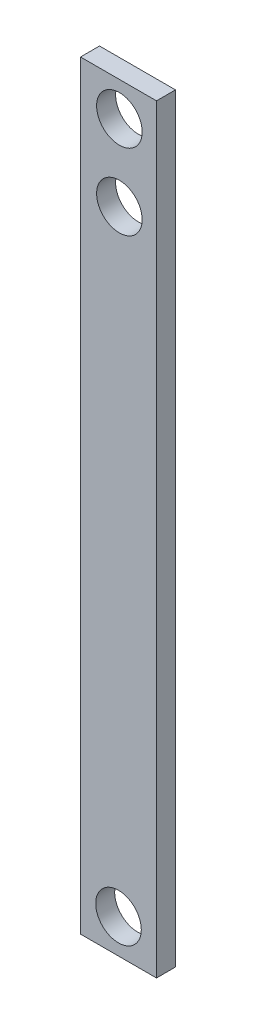
SolidWorks part; units mm, degrees
ref_plane "Front Plane" through (0, 0, 0) normal (0, 0, 1) x (1, 0, 0)
ref_plane "Top Plane" through (0, 0, 0) normal (0, 1, 0) x (1, 0, 0)
ref_plane "Right Plane" through (0, 0, 0) normal (1, 0, 0) x (0, 0, -1)
sketch "Sketch1" plane through (0, 0, 0) normal (0, 0, 1) x (1, 0, 0)
  line L1 (0, 0) -> (10, 0)
  line L2 (0, 0) -> (0, 100)
  line L3 (0, 100) -> (10, 100)
  line L4 (10, 0) -> (10, 100)
  dimension "D1" = 10
  dimension "D2" = 100
extrude "Boss-Extrude1" add sketch "Sketch1" along normal blind 2.5 contours L2 L3 L4 L1
sketch "Sketch2" plane through (0, 0, 2.5) normal (0, 0, 1) x (1, 0, 0)
  line L0 (0, 0) -> (10, 0) construction
  circle A0 centre (5, 4.5) radius 3
  point P4 (5, 0)
  dimension "D1" = 6
  dimension "D2" = 4.5
  dimension "D3" = 0
extrude "Cut-Extrude1" cut sketch "Sketch2" against normal through all
sketch "Sketch3" plane through (0, 0, 2.5) normal (0, 0, 1) x (1, 0, 0)
  line L0 (0, 100) -> (10, 100) construction
  circle A0 centre (5.115, 95.5) radius 3
  dimension "D1" = 6
  dimension "D2" = 4.5
sketch "Sketch5" plane through (0, 0, 2.5) normal (0, 0, 1) x (1, 0, 0)
  circle A0 centre (5.115, 85.5) radius 3
  dimension "D1" = 6
  dimension "D2" = 0
  dimension "D3" = 10
extrude "Cut-Extrude2" cut sketch "Sketch5" against normal through all
extrude "Cut-Extrude3" cut sketch "Sketch3" against normal blind 10
